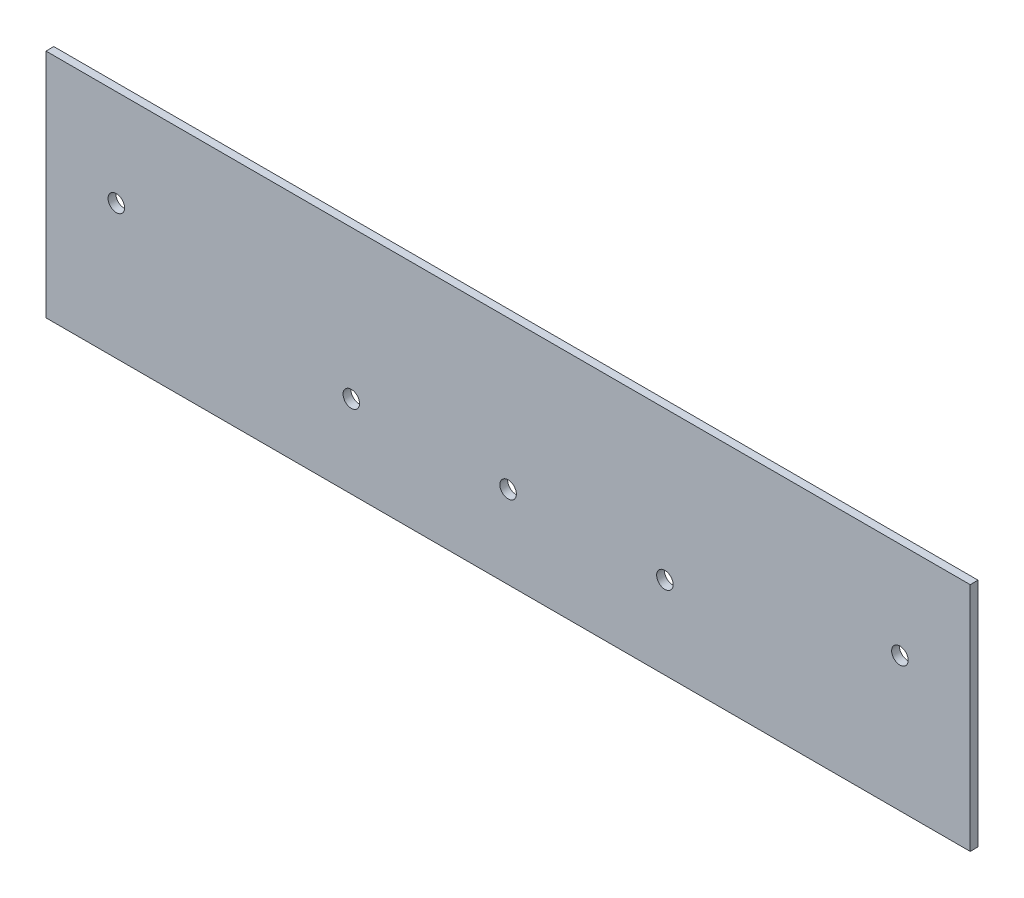
SolidWorks part; units mm, degrees
ref_plane "Front Plane" through (0, 0, 0) normal (0, 0, 1) x (1, 0, 0)
ref_plane "Top Plane" through (0, 0, 0) normal (0, 1, 0) x (1, 0, 0)
ref_plane "Right Plane" through (0, 0, 0) normal (1, 0, 0) x (0, 0, -1)
sketch "Sketch1" plane through (0, 0, 0) normal (0, 0, 1) x (1, 0, 0)
  line L1 (-177.8, -57.15) -> (177.8, -57.15)
  line L2 (-177.8, -57.15) -> (-177.8, 57.15)
  line L3 (-177.8, 57.15) -> (177.8, 57.15)
  line L4 (177.8, -57.15) -> (177.8, 57.15)
  line L5 (-177.8, -57.15) -> (177.8, 57.15) construction
  line L6 (-177.8, 57.15) -> (177.8, -57.15) construction
  point P0 (0, 0)
  dimension "D1" = 355.6
  dimension "D2" = 114.3
extrude "Boss-Extrude1" add sketch "Sketch1" along normal blind 3
sketch "Sketch3" plane through (0, 0, 3) normal (0, 0, 1) x (1, 0, 0)
  line L0 (0, 92.3884) -> (0, -106.1191) construction
  line L1 (102.534, -107.8807) -> (162.859, -107.8807) construction
  line L2 (102.534, -107.8807) -> (102.534, -87.8807) construction
  line L3 (102.534, -87.8807) -> (12.11, -87.8807) construction
  line L4 (132.6965, -107.8807) -> (132.6965, -116.3437) construction
  line L5 (-60.325, 0) -> (0, 0) construction
  line L6 (-60.325, 0) -> (-60.325, 20) construction
  line L7 (-60.325, 20) -> (-150.749, 20) construction
  line L8 (-30.1625, 0) -> (-30.1625, -8.4631) construction
  circle A0 centre (102.534, -107.8807) radius 3.175 construction
  circle A1 centre (162.859, -107.8807) radius 3.175 construction
  circle A2 centre (12.11, -87.8807) radius 3.175 construction
  circle A12 centre (-60.325, 0) radius 3.175
  circle A13 centre (0, 0) radius 3.175
  circle A14 centre (-150.749, 20) radius 3.175
  dimension "D2" = 6.35
  dimension "D5" = 6.35
  dimension "D7" = 6.35
  dimension "D10" = 6.35
  dimension "D1" = 60.325
  dimension "D3" = 20
  dimension "D4" = 90.424
  dimension "D6" = 60.325
  dimension "D8" = 20
  dimension "D9" = 90.424
extrude "Cut-Extrude1" cut sketch "Sketch3" against normal up to surface (3 mm away) up to face at (0, 0, 0)
ref_plane "Plane1" through (0, 0, 0) normal (1, 0, 0) x (0, 0, -1)
mirror "Mirror3" about plane through (0, 0, 0) normal (1, 0, 0) of "Cut-Extrude1"
sketch "Sketch4" plane through (0, 0, 0) normal (0, 0, -1) x (-1, 0, 0)
  line L0 (177.8, 57.15) -> (177.8, -57.15) construction
  line L1 (-177.8, -57.15) -> (177.8, -57.15)
  line L2 (-177.8, -57.15) -> (-177.8, -31.75)
  line L3 (-177.8, -31.75) -> (177.8, -31.75)
  line L4 (177.8, -57.15) -> (177.8, -31.75)
  dimension "D1" = 25.4
extrude "Cut-Extrude2" cut sketch "Sketch4" against normal up to next
